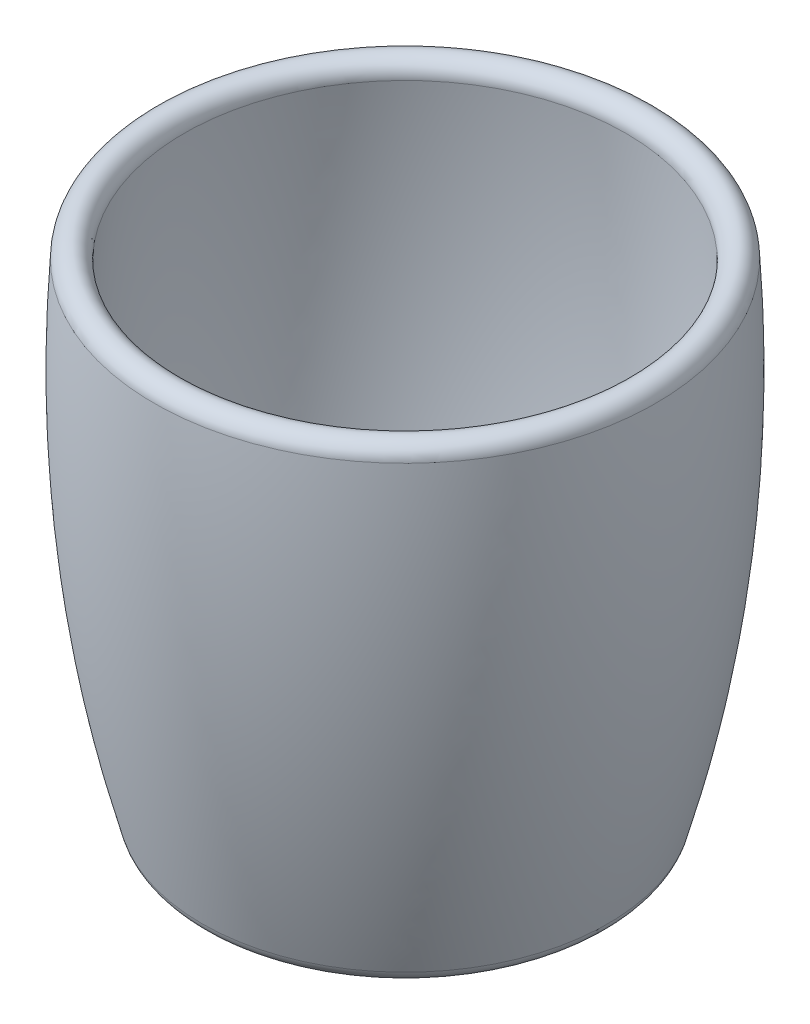
SolidWorks part; units mm, degrees
material "Epoxy, Unfilled"
ref_plane "Front Plane" through (0, 0, 0) normal (0, 0, 1) x (1, 0, 0)
ref_plane "Top Plane" through (0, 0, 0) normal (0, 1, 0) x (1, 0, 0)
ref_plane "Right Plane" through (0, 0, 0) normal (1, 0, 0) x (0, 0, -1)
sketch "Sketch1" plane through (0, 0, 0) normal (0, 0, 1) x (1, 0, 0)
  line L0 (0, 0) -> (33.25, 0)
  line L1 (0, 0) -> (0, 94.0651) construction
  line L2 (40, 0) -> (40, 91.6533) construction
  line L3 (55.8028, 78.6511) -> (10.6972, -78.6511) construction
  line L4 (0, 5) -> (29.4504, 5)
  line L5 (0, 5) -> (0, 0)
  arc A0 (36.8601, 81.0826) -> (41.85, 81.4) centre (39.355, 81.2413) cw
  spline S0 degree 2 poles (33.25, 0) (44.5264, 39.3255) (41.85, 81.4) knots 0 0 0 1 1 1
  spline S1 degree 1 poles (29.4504, 5) (36.8601, 81.0826) knots 0 0 1 1 construction
  spline S2 degree 2 poles (29.4504, 5) (39.3569, 41.7805) (36.8601, 81.0826) knots 0.04697 0.04697 0.04697 1 1 1
  point P4 (40.0807, 32.2)
  dimension "D1" = 81.4
  dimension "D2" = 83.7
  dimension "D3" = 66.5
  dimension "D4" = 32.2
  dimension "D5" = 40
  dimension "D6" = 74
  dimension "D8" = 81.2413
  dimension "D7" = 5
revolve "Revolve1" add sketch "Sketch1" angle 360 about L1
fillet "Fillet1" radius 3 2 edges at (0, 0, -33.25) (0, 5, -29.4504)
